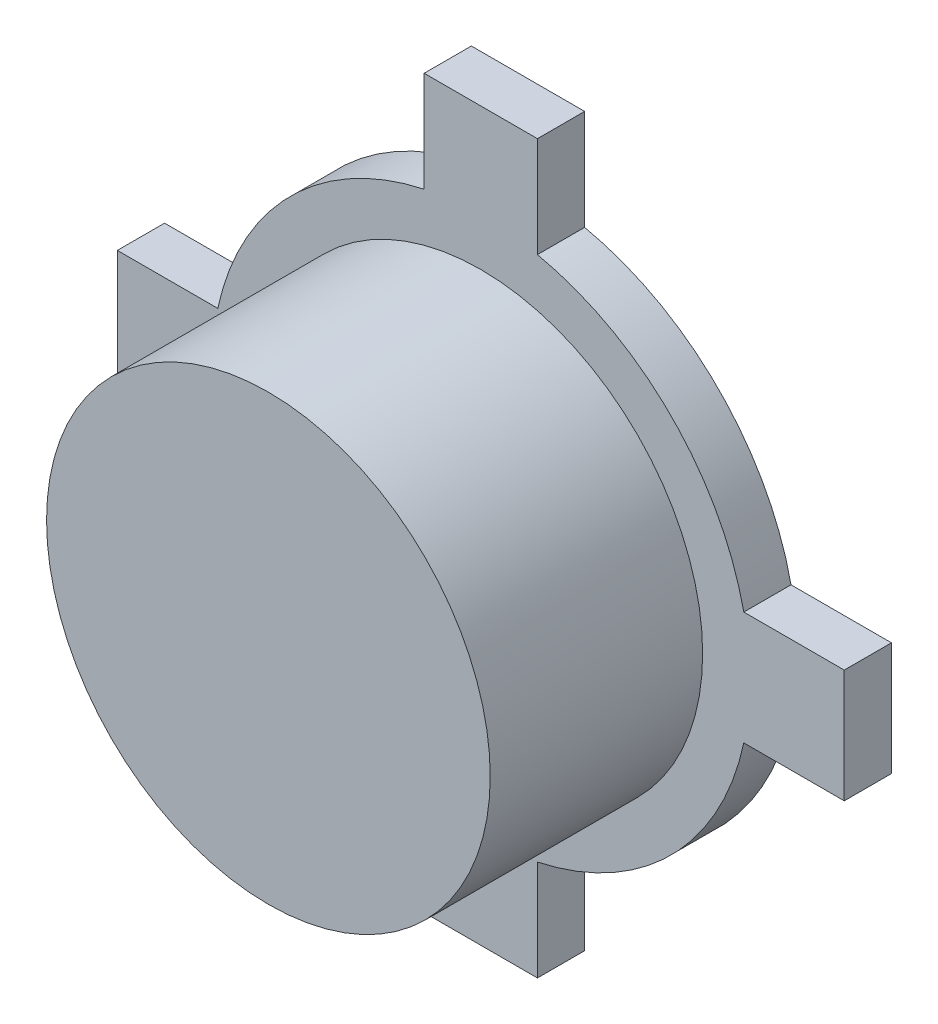
SolidWorks part; units mm, degrees
ref_plane "Front Plane" through (0, 0, 0) normal (0, 0, 1) x (1, 0, 0)
ref_plane "Top Plane" through (0, 0, 0) normal (0, 1, 0) x (1, 0, 0)
ref_plane "Right Plane" through (0, 0, 0) normal (1, 0, 0) x (0, 0, -1)
sketch "Sketch1" plane through (0, 0, 0) normal (0, 0, 1) x (1, 0, 0)
  circle A0 centre (0, 0) radius 4.7
  circle A1 centre (0, 0) radius 5 construction
  dimension "D1" = 0.3
extrude "Boss-Extrude1" add sketch "Sketch1" along normal blind 4.5
sketch "Sketch2" plane through (0, 0, 0) normal (0, 0, -1) x (-1, 0, 0)
  line L110 (-5.5723, 1.2) -> (-7.7, 1.2)
  line L111 (-7.7, 1.2) -> (-7.7, -1.2)
  line L112 (-7.7, -1.2) -> (-5.5723, -1.2)
  line L113 (-1.2, -5.5723) -> (-1.2, -7.7)
  line L114 (-1.2, -7.7) -> (1.2, -7.7)
  line L115 (1.2, -7.7) -> (1.2, -5.5723)
  line L116 (5.5723, -1.2) -> (7.7, -1.2)
  line L117 (7.7, -1.2) -> (7.7, 1.2)
  line L118 (7.7, 1.2) -> (5.5723, 1.2)
  line L119 (1.2, 5.5723) -> (1.2, 7.7)
  line L120 (-1.2, 7.7) -> (-1.2, 5.5723)
  line L121 (1.2, 7.7) -> (-1.2, 7.7)
  line L122 (-5.5723, 1.2) -> (-7.7, 1.2)
  line L123 (-7.7, 1.2) -> (-7.7, -1.2)
  line L124 (-7.7, -1.2) -> (-5.5723, -1.2)
  line L125 (-1.2, -5.5723) -> (-1.2, -7.7)
  line L126 (-1.2, -7.7) -> (1.2, -7.7)
  line L127 (1.2, -7.7) -> (1.2, -5.5723)
  line L128 (5.5723, -1.2) -> (7.7, -1.2)
  line L129 (7.7, -1.2) -> (7.7, 1.2)
  line L130 (7.7, 1.2) -> (5.5723, 1.2)
  line L131 (1.2, 5.5723) -> (1.2, 7.7)
  line L132 (-1.2, 7.7) -> (-1.2, 5.5723)
  line L133 (1.2, 7.7) -> (-1.2, 7.7)
  arc A42 (-5.5723, -1.2) -> (-1.2, -5.5723) centre (0, 0) ccw
  arc A43 (1.2, -5.5723) -> (5.5723, -1.2) centre (0, 0) ccw
  arc A44 (5.5723, 1.2) -> (1.2, 5.5723) centre (0, 0) ccw
  arc A45 (-1.2, 5.5723) -> (-5.5723, 1.2) centre (0, 0) ccw
  arc A46 (-5.5723, -1.2) -> (-1.2, -5.5723) centre (0, 0) ccw
  arc A47 (1.2, -5.5723) -> (5.5723, -1.2) centre (0, 0) ccw
  arc A48 (5.5723, 1.2) -> (1.2, 5.5723) centre (0, 0) ccw
  arc A49 (-1.2, 5.5723) -> (-5.5723, 1.2) centre (0, 0) ccw
  dimension "D1" = 0.3
extrude "Boss-Extrude2" add sketch "Sketch2" along normal blind 1
